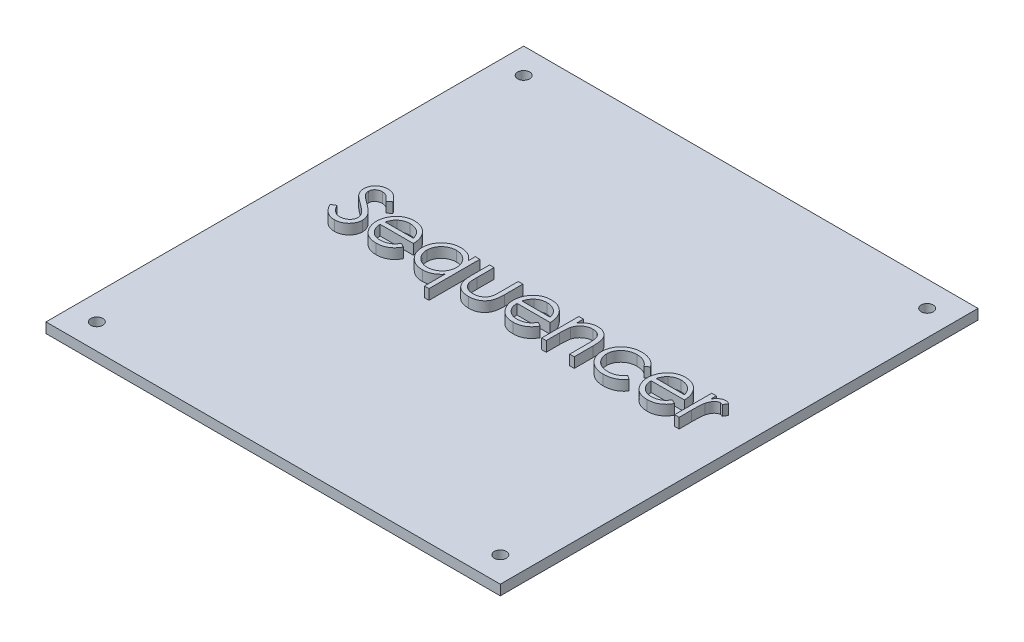
SolidWorks part; units mm, degrees
ref_plane "Front Plane" through (0, 0, 0) normal (0, 0, 1) x (1, 0, 0)
ref_plane "Top Plane" through (0, 0, 0) normal (0, 1, 0) x (1, 0, 0)
ref_plane "Right Plane" through (0, 0, 0) normal (1, 0, 0) x (0, 0, -1)
sketch "Sketch1" plane through (0, 0, 0) normal (0, 1, 0) x (1, 0, 0)
  line L1 (56.769, -59.69) -> (-56.769, -59.69)
  line L2 (56.769, -59.69) -> (56.769, 59.69)
  line L3 (56.769, 59.69) -> (-56.769, 59.69)
  line L4 (-56.769, -59.69) -> (-56.769, 59.69)
  line L5 (56.769, -59.69) -> (-56.769, 59.69) construction
  line L6 (56.769, 59.69) -> (-56.769, -59.69) construction
  point P0 (0, 0)
  dimension "D1" = 119.38
  dimension "D2" = 113.538
extrude "Boss-Extrude1" add sketch "Sketch1" along normal blind 2.54
sketch "Sketch2" plane through (0, 2.54, 0) normal (0, 1, 0) x (1, 0, 0)
  text T0 "Sequencer" font "Century Gothic" height in points 48
extrude "Boss-Extrude2" add sketch "Sketch2" along normal blind 2.54
hole_wizard "Ø3.0mm Dowel Hole1" positions "Sketch7" profile "Sketch8" hole size "Ø3.0" standard "AS" end condition through all
sketch "Sketch7" plane through (0, 2.54, 0) normal (0, 1, 0) x (1, 0, 0)
  line L0 (-56.769, 59.69) -> (-56.769, -59.69) construction
  line L1 (56.769, 59.69) -> (-56.769, 59.69) construction
  line L3 (-56.769, -59.69) -> (56.769, -59.69) construction
  line L4 (56.769, -59.69) -> (56.769, 59.69) construction
  point P0 (-50.419, 53.34)
  point P2 (50.419, 53.34)
  point P4 (-50.419, -53.34)
  point P6 (50.419, -53.34)
  dimension "D1" = 6.35
  dimension "D2" = 6.35
  dimension "D3" = 6.35
  dimension "D4" = 6.35
  dimension "D5" = 6.35
  dimension "D6" = 6.35
  dimension "D7" = 6.35
  dimension "D8" = 6.35
sketch "Sketch8" plane through (-50.419, 2.54, -53.34) normal (1, 0, 0) x (0, 0, 1)
  line L0 (0, 0) -> (0, 2.54)
  line L1 (0, 2.54) -> (1.5, 2.54)
  line L2 (1.5, 2.54) -> (1.5, 0)
  line L5 (1.5, 0) -> (0, 0)
  line L11 (0, -6.35) -> (0, 107.95) construction
  dimension "Thru Hole Dia." = 3
  dimension "Thru Hole Depth" = 2.54
